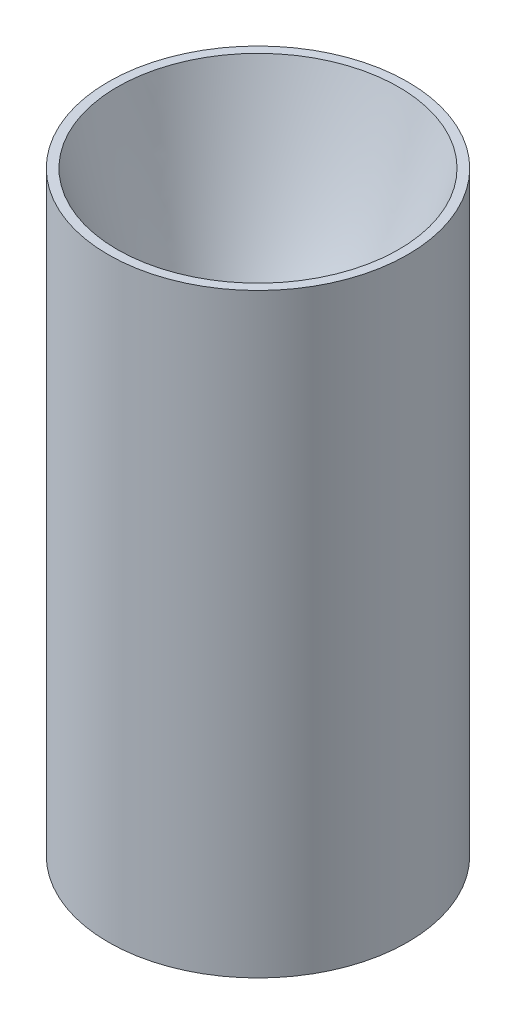
SolidWorks part; units mm, degrees
ref_plane "Front Plane" through (0, 0, 0) normal (0, 0, 1) x (1, 0, 0)
ref_plane "Top Plane" through (0, 0, 0) normal (0, 1, 0) x (1, 0, 0)
ref_plane "Right Plane" through (0, 0, 0) normal (1, 0, 0) x (0, 0, -1)
sketch "Sketch1" plane through (0, 0, 0) normal (0, 0, 1) x (1, 0, 0)
  line L0 (24.01, 0) -> (0, 0) construction
  line L1 (71.6385, 109.9273) -> (76.2, 109.9273)
  line L4 (53.7925, -59.7277) -> (53.7925, -212.1277)
  line L9 (76.2, 109.9273) -> (76.2, -212.1277)
  line L10 (76.2, -212.1277) -> (53.7925, -212.1277)
  line L11 (0, 0) -> (0, -107.6606) construction
  spline S0 degree 2 poles (26.7062, 6.5092) (49.1723, 34.636) (71.6385, 109.9273) knots 0 0 0 1 1 1 construction
  spline S1 degree 2 poles (26.7062, 6.5092) (49.1723, 34.636) (71.6385, 109.9273) knots 0 0 0 1 1 1
  spline S2 degree 4 poles (24.0378, -0.7181) (24.0369, -0.702) (24.0352, -0.674) (24.0319, -0.6548) (24.026, -0.5168) (24.0168, -0.4371) (24.0103, -0.1068) (24.0089, 0.0016) (24.013, 0.2676) (24.0194, 0.4271) (24.0315, 0.6468) (24.0524, 0.9014) (24.0861, 1.2025) (24.1374, 1.5421) (24.2015, 1.881) (24.2781, 2.2164) (24.3673, 2.5492) (24.4687, 2.8781) (24.5826, 3.2033) (24.7081, 3.5236) (24.8462, 3.8397) (24.995, 4.1493) (25.1569, 4.4548) (25.3274, 4.7513) (25.5134, 5.0457) (25.7027, 5.3255) (25.9153, 5.6107) (26.0898, 5.8329) (26.2773, 6.05) (26.4155, 6.2086) (26.6679, 6.4727) (26.7479, 6.5524) (27.0125, 6.8058) (27.099, 6.8781) (27.1963, 6.9666) (27.2147, 6.9802) (27.2373, 7.0002) knots 0 0 0 0 0 0.005192 0.010384 0.020768 0.041536 0.082569 0.102427 0.122284 0.142142 0.162 0.201716 0.241431 0.281147 0.320863 0.360578 0.400294 0.44001 0.479725 0.519441 0.559156 0.598872 0.638588 0.678303 0.718019 0.757735 0.79745 0.837166 0.857024 0.876882 0.916597 0.958047 0.979024 0.989512 1 1 1 1 1 construction
  spline S3 degree 4 poles (24.01, 0) (24.01, 0.0359) (24.0105, 0.1101) (24.013, 0.2676) (24.0194, 0.4271) (24.0315, 0.6468) (24.0524, 0.9014) (24.0861, 1.2025) (24.1374, 1.5421) (24.2015, 1.881) (24.2781, 2.2164) (24.3673, 2.5492) (24.4687, 2.8781) (24.5826, 3.2033) (24.7081, 3.5236) (24.8462, 3.8397) (24.995, 4.1493) (25.1569, 4.4548) (25.3274, 4.7513) (25.5134, 5.0457) (25.7027, 5.3255) (25.9153, 5.6107) (26.0898, 5.8329) (26.2773, 6.05) (26.4155, 6.2086) (26.5814, 6.3821) (26.6555, 6.4585) (26.7062, 6.5092) knots 0.082569 0.082569 0.082569 0.082569 0.082569 0.102427 0.122284 0.142142 0.162 0.201716 0.241431 0.281147 0.320863 0.360578 0.400294 0.44001 0.479725 0.519441 0.559156 0.598872 0.638588 0.678303 0.718019 0.757735 0.79745 0.837166 0.857024 0.876882 0.916597 0.916597 0.916597 0.916597 0.916597
  spline S4 degree 4 poles (24.1192, 2.8078) (24.1123, 2.7164) (24.0991, 2.5516) (24.0751, 2.1752) (24.0462, 1.6879) (24.0258, 1.1016) (24.0139, 0.6554) (24.0097, 0.1102) (24.0097, -0.1001) (24.0129, -0.5432) (24.0192, -0.8242) (24.0287, -1.1948) (24.0414, -1.5134) (24.0572, -1.8619) (24.0761, -2.1937) (24.1038, -2.6181) (24.1432, -3.122) (24.2142, -3.88) (24.3341, -4.8865) (24.5104, -6.0567) (24.7618, -7.3852) (25.0627, -8.7036) (25.4127, -10.0096) (25.8113, -11.3018) (26.2579, -12.5781) (26.7519, -13.8369) (27.2926, -15.0762) (27.8794, -16.2946) (28.5111, -17.4899) (29.1875, -18.6613) (29.9064, -19.8057) (30.669, -20.9239) (31.3701, -21.8744) (31.9997, -22.6734) (32.5351, -23.3204) (32.9832, -23.84) (33.4194, -24.3298) (33.8468, -24.7885) (34.1565, -25.1139) (34.523, -25.486) (34.677, -25.64) (35.0618, -26.0189) (35.3885, -26.3288) (35.8159, -26.7274) (36.1505, -27.0244) (36.4301, -27.2709) (36.5574, -27.38) (36.6257, -27.4388) (36.6605, -27.4687) knots 0 0 0 0 0 0.010393 0.020785 0.041571 0.062104 0.072371 0.082638 0.092575 0.102512 0.112449 0.122387 0.132324 0.142261 0.152198 0.162135 0.18201 0.201884 0.241633 0.281382 0.32113 0.360879 0.400628 0.440377 0.480126 0.519874 0.559623 0.599372 0.639121 0.67887 0.718618 0.758367 0.798116 0.81799 0.837865 0.857739 0.877613 0.897488 0.907425 0.917362 0.927629 0.937896 0.958429 0.979215 0.989607 0.994804 1 1 1 1 1 construction
  spline S5 degree 4 poles (24.01, 0) (24.01, -0.0705) (24.0105, -0.2136) (24.0129, -0.5432) (24.0192, -0.8242) (24.0287, -1.1948) (24.0414, -1.5134) (24.0572, -1.8619) (24.0761, -2.1937) (24.1038, -2.6181) (24.1432, -3.122) (24.2142, -3.88) (24.3341, -4.8865) (24.5104, -6.0567) (24.7618, -7.3852) (25.0627, -8.7036) (25.4127, -10.0096) (25.8113, -11.3018) (26.2579, -12.5781) (26.7519, -13.8369) (27.2926, -15.0762) (27.8794, -16.2946) (28.5111, -17.4899) (29.1875, -18.6613) (29.9064, -19.8057) (30.669, -20.9239) (31.3701, -21.8744) (31.9997, -22.6734) (32.5351, -23.3204) (32.9832, -23.84) (33.4194, -24.3298) (33.8468, -24.7885) (34.1565, -25.1139) (34.4478, -25.4096) (34.5473, -25.5099) (34.5972, -25.5598) knots 0.082638 0.082638 0.082638 0.082638 0.082638 0.092575 0.102512 0.112449 0.122387 0.132324 0.142261 0.152198 0.162135 0.18201 0.201884 0.241633 0.281382 0.32113 0.360879 0.400628 0.440377 0.480126 0.519874 0.559623 0.599372 0.639121 0.67887 0.718618 0.758367 0.798116 0.81799 0.837865 0.857739 0.877613 0.897488 0.907425 0.917362 0.917362 0.917362 0.917362 0.917362
  spline S6 degree 1 poles (34.5972, -25.5598) (43.2048, -34.1675) knots 0 0 1 1 construction
  spline S7 degree 1 poles (34.5972, -25.5598) (43.2048, -34.1675) knots 0 0 1 1
  spline S8 degree 4 poles (53.6833, -62.5354) (53.6902, -62.4466) (53.7033, -62.2738) (53.7213, -62.0018) (53.7419, -61.6601) (53.7589, -61.2922) (53.7725, -60.9659) (53.7826, -60.5754) (53.7894, -60.2941) (53.7927, -59.8333) (53.7927, -59.6305) (53.7896, -59.1817) (53.7832, -58.905) (53.7737, -58.5327) (53.7611, -58.213) (53.7414, -57.7818) (53.7113, -57.2811) (53.6671, -56.6882) (53.5882, -55.8486) (53.4884, -55.0083) (53.3676, -54.1726) (53.1977, -53.1726) (53.003, -52.1776) (52.7773, -51.1887) (52.5209, -50.2076) (52.2402, -49.2332) (51.9353, -48.2661) (51.5445, -47.1493) (51.0505, -45.8906) (50.5097, -44.6511) (49.923, -43.4329) (49.2911, -42.2373) (48.6151, -41.0663) (47.8954, -39.9211) (47.134, -38.8042) (46.4308, -37.8516) (45.8045, -37.0558) (45.2637, -36.4035) (44.8261, -35.8944) (44.4257, -35.4472) (44.0924, -35.0848) (43.7849, -34.7605) (43.585, -34.5517) (43.2762, -34.2384) (43.1268, -34.0891) (42.7386, -33.7068) (42.415, -33.3999) (41.985, -32.9988) (41.6521, -32.7035) (41.3716, -32.4561) (41.2447, -32.3474) (41.1763, -32.2885) (41.1415, -32.2585) knots 0 0 0 0 0 0.010393 0.020785 0.031178 0.041571 0.051838 0.062104 0.072371 0.082638 0.092575 0.102512 0.112449 0.122387 0.132324 0.142261 0.162135 0.18201 0.201884 0.241633 0.261507 0.281382 0.32113 0.360879 0.380754 0.400628 0.440377 0.480126 0.519874 0.559623 0.599372 0.639121 0.67887 0.718618 0.758367 0.798116 0.81799 0.837865 0.857739 0.877613 0.887551 0.897488 0.907425 0.917362 0.927629 0.937896 0.958429 0.979215 0.989607 0.994804 1 1 1 1 1 construction
  spline S9 degree 4 poles (53.7925, -59.7277) (53.7925, -59.6571) (53.7919, -59.5156) (53.7896, -59.1817) (53.7832, -58.905) (53.7737, -58.5327) (53.7611, -58.213) (53.7414, -57.7818) (53.7113, -57.2811) (53.6671, -56.6882) (53.5882, -55.8486) (53.4884, -55.0083) (53.3676, -54.1726) (53.1977, -53.1726) (53.003, -52.1776) (52.7773, -51.1887) (52.5209, -50.2076) (52.2402, -49.2332) (51.9353, -48.2661) (51.5445, -47.1493) (51.0505, -45.8906) (50.5097, -44.6511) (49.923, -43.4329) (49.2911, -42.2373) (48.6151, -41.0663) (47.8954, -39.9211) (47.134, -38.8042) (46.4308, -37.8516) (45.8045, -37.0558) (45.2637, -36.4035) (44.8261, -35.8944) (44.4257, -35.4472) (44.0924, -35.0848) (43.7849, -34.7605) (43.585, -34.5517) (43.3553, -34.3187) (43.2547, -34.2173) (43.2048, -34.1675) knots 0.082638 0.082638 0.082638 0.082638 0.082638 0.092575 0.102512 0.112449 0.122387 0.132324 0.142261 0.162135 0.18201 0.201884 0.241633 0.261507 0.281382 0.32113 0.360879 0.380754 0.400628 0.440377 0.480126 0.519874 0.559623 0.599372 0.639121 0.67887 0.718618 0.758367 0.798116 0.81799 0.837865 0.857739 0.877613 0.887551 0.897488 0.907425 0.917362 0.917362 0.917362 0.917362 0.917362
  spline S10 degree 2 poles (36.8348, 6.4922) (58.5888, 47.6142) (81.7275, 109.9275) knots 0.466481 0.466481 0.466481 0.998147 0.998147 0.998147 construction
  dimension "D1" = 152.4
  dimension "D2" = 24.01
  dimension "D3" = 152.4
revolve "Revolve2" add sketch "Sketch1" angle 360 about L11
other "shorten_chamber_.75in" face at (0, -212.1277, 76.2) parameters "D1"=19.05
hole_wizard "3/8-24 Tapped Hole1" positions "Sketch3" profile "Sketch4" tap size "3/8-24" standard "ANSI Inch"
sketch "Sketch3" plane through (0, -193.0777, 0) normal (0, -1, 0) x (-1, 0, 0)
  circle A1 centre (0, 0) radius 66.675 construction
  point P10 (-66.675, 0)
  dimension "D1" = 133.35
sketch "Sketch4" plane through (66.675, -193.0777, 0) normal (1, 0, 0) x (0, 0, -1)
  line L0 (0, 0) -> (0, 27.5347)
  line L1 (0, 27.5347) -> (4.2164, 25.0012)
  line L2 (4.2164, 25.0012) -> (4.2164, 0)
  line L5 (4.2164, 0) -> (0, 0)
  line L10 (0, 27.5347) -> (-4.2164, 25.0012) construction
  line L11 (0, -6.35) -> (0, 107.95) construction
  dimension "Tap Drill Dia." = 8.4328
  dimension "Tap Drill Depth" = 25.0012
  dimension "Drill Angle" = 118
cosmetic thread "Hole Thread1" parameters "D1"=20, "D2"=9.525
pattern_circular "CirPattern1" count 8 over 360 about axis through (0, 0, 0) along (0, 1, 0) of "3/8-24 Tapped Hole1"
cosmetic thread "Hole Thread2" parameters "D1"=20, "D2"=9.525
cosmetic thread "Hole Thread3" parameters "D1"=20, "D2"=9.525
cosmetic thread "Hole Thread4" parameters "D1"=20, "D2"=9.525
cosmetic thread "Hole Thread5" parameters "D1"=20, "D2"=9.525
cosmetic thread "Hole Thread6" parameters "D1"=20, "D2"=9.525
cosmetic thread "Hole Thread7" parameters "D1"=20, "D2"=9.525
cosmetic thread "Hole Thread8" parameters "D1"=20, "D2"=9.525
sketch "Sketch8" [suppressed] plane through (0, -212.1275, 0) normal (0, -1, 0) x (1, 0, 0)
  circle A0 centre (0, 0) radius 53.8815 construction
  circle A1 centre (0, 0) radius 76.49 construction
  circle A2 centre (0, 0) radius 65.2002 construction
  dimension "D1" = 107.7631
  dimension "D2" = 130.4004
  dimension "D3" = 152.98
sketch "Sketch9" [suppressed] plane through (0, -212.1277, 0) normal (0, -1, 0) x (1, 0, 0)
  circle A0 centre (0, 0) radius 53.8815
  circle A1 centre (0, 0) radius 56.8815
  dimension "D1" = 3
extrude "Cut-Extrude1" [suppressed] cut sketch "Sketch9" against normal blind 6
hole_wizard "1/4 (0.2500) Dowel Hole1" [suppressed] positions "Sketch11" profile "Sketch12" hole size "1/4" standard "ANSI Inch"
sketch "Sketch11" plane through (0, -212.1277, 0) normal (0, -1, 0) x (-1, 0, 0)
  line L6 (0, 0) -> (61.5997, -25.5154) construction
  line L8 (0, 0) -> (-61.5997, 25.5154) construction
  line L9 (0, 0) -> (-66.675, 0) construction
  circle A0 centre (0, 0) radius 66.675 construction
  point P22 (61.5997, -25.5154)
  point P28 (-61.5997, 25.5154)
  dimension "D1" = 22.5
sketch "Sketch12" plane through (61.5997, -212.1277, -25.5154) normal (1, 0, 0) x (0, 0, -1)
  line L0 (0, 0) -> (0, 11.829)
  line L1 (0, 11.829) -> (3.2004, 9.906)
  line L2 (3.2004, 9.906) -> (3.2004, 0)
  line L5 (3.2004, 0) -> (0, 0)
  line L10 (0, 11.829) -> (-3.2004, 9.906) construction
  line L11 (0, -6.35) -> (0, 107.95) construction
  dimension "Hole Dia." = 6.4008
  dimension "Hole Depth" = 9.906
  dimension "Drill Angle" = 118
sketch "Sketch14" plane through (0, -193.0777, 0) normal (0, -1, 0) x (1, 0, 0)
  circle A0 centre (0, 0) radius 53.7925 construction
  circle A1 centre (0, 0) radius 53.7925 construction
  circle A2 centre (0, 0) radius 55.38
  circle A3 centre (0, 0) radius 57.412
  dimension "D1" = 1.5875
  dimension "D2" = 2.032
extrude "gasket_groove" [suppressed] cut sketch "Sketch14" against normal blind 1.27
